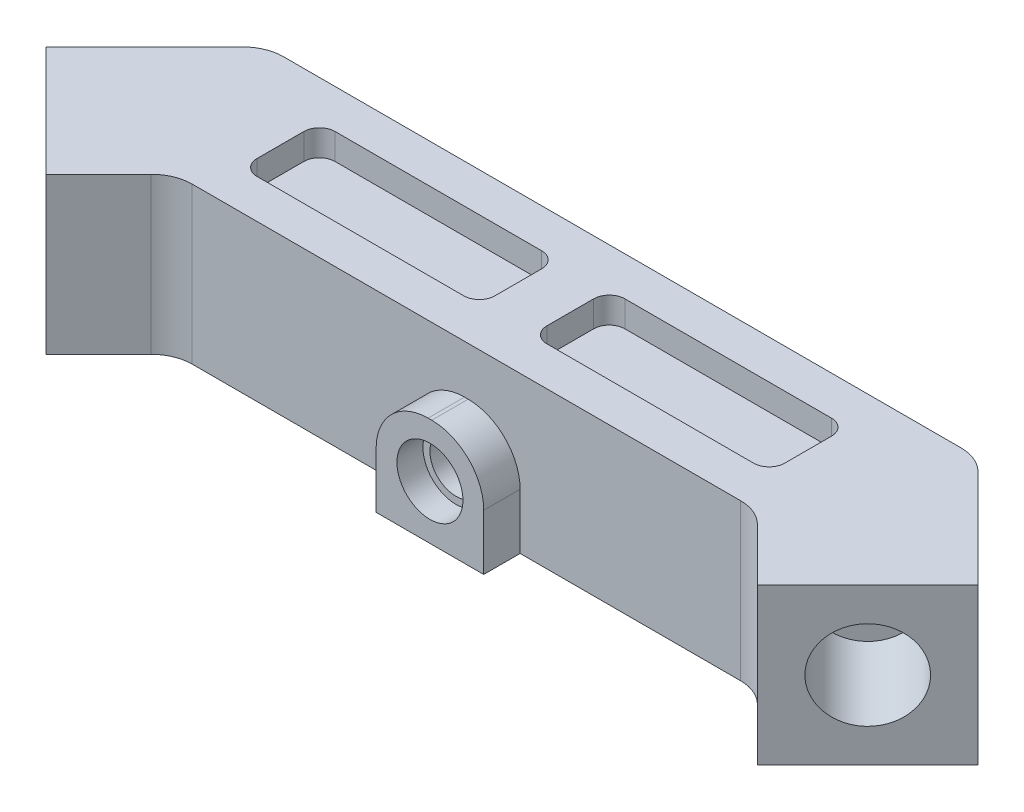
SolidWorks part; units mm, degrees
ref_plane "Front Plane" through (0, 0, 0) normal (0, 0, 1) x (1, 0, 0)
ref_plane "Top Plane" through (0, 0, 0) normal (0, 1, 0) x (1, 0, 0)
ref_plane "Right Plane" through (0, 0, 0) normal (1, 0, 0) x (0, 0, -1)
sketch "Sketch1" plane through (0, 0, 0) normal (0, 1, 0) x (1, 0, 0)
  line L1 (0, 0) -> (142.24, 0)
  line L3 (-15.7815, 38.1) -> (158.0215, 38.1)
  line L5 (0, 0) -> (-15.7815, -15.7815)
  line L6 (-42.7223, 11.1592) -> (-15.7815, -15.7815)
  line L7 (71.12, 38.1) -> (71.12, 0) construction
  line L8 (142.24, 0) -> (158.0215, -15.7815)
  line L9 (184.9623, 11.1592) -> (158.0215, -15.7815)
  line L10 (158.0215, 38.1) -> (184.9623, 11.1592)
  line L11 (-15.7815, 38.1) -> (-42.7223, 11.1592)
  dimension "D1" = 38.1
  dimension "D2" = 135
  dimension "D3" = 38.1
  dimension "D4" = 90
  dimension "D5" = 38.1
  dimension "D6" = 90
  dimension "D7" = 38.1
  dimension "D8" = 38.1
  dimension "D9" = 90
  dimension "D10" = 90
  dimension "D11" = 38.1
  dimension "D12" = 22.3185
  dimension "D13" = 142.24
  dimension "D14" = 173.8031
extrude "Boss-Extrude1" add sketch "Sketch1" along normal blind 38.1
sketch "Sketch2" plane through (-15.7815, 0, 15.7815) normal (-0.7071, 0, 0.7071) x (0.7071, 0, 0.7071)
  line L0 (-38.1, 38.1) -> (0, 0) construction
  line L1 (-38.1, 0) -> (0, 38.1) construction
  circle A0 centre (-19.05, 19.05) radius 10.8585
  dimension "D1" = 21.717
extrude "Cut-Extrude1" cut sketch "Sketch2" against normal blind 25.4
sketch "Sketch3" plane through (86.9015, 0, 86.9015) normal (0.7071, 0, 0.7071) x (0.7071, 0, -0.7071)
  line L0 (100.5789, 38.1) -> (138.6789, 0) construction
  line L1 (100.5789, 0) -> (138.6789, 38.1) construction
  circle A0 centre (119.6289, 19.05) radius 10.8585
  point P11 (119.6289, 19.05)
  dimension "D1" = 21.717
extrude "Cut-Extrude2" cut sketch "Sketch3" against normal blind 25.4
fillet "Fillet1" radius 10 2 edges at (142.24, 19.05, 0) (0, 19.05, 0)
fillet "Fillet2" radius 10 2 edges at (158.0215, 19.05, -38.1) (-15.7815, 19.05, -38.1)
sketch "Sketch5" plane through (0, 0, 0) normal (0, 0, 1) x (1, 0, 0)
  line L0 (4.1421, 0) -> (138.0979, 0) construction
  line L1 (57.9755, 0) -> (84.2645, 0)
  line L2 (57.9755, 0) -> (57.9755, 26.289)
  line L3 (57.9755, 26.289) -> (84.2645, 26.289)
  line L4 (84.2645, 0) -> (84.2645, 26.289)
  line L5 (4.1421, 38.1) -> (138.0979, 38.1) construction
  point P8 (71.12, 38.1)
  point P9 (71.12, 26.289)
  dimension "D1" = 26.289
  dimension "D2" = 26.289
extrude "Boss-Extrude2" add sketch "Sketch5" along normal blind 8.89
sketch "Sketch6" plane through (0, 0, 8.89) normal (0, 0, 1) x (1, 0, 0)
  line L0 (84.2645, 26.289) -> (57.9755, 26.289) construction
  line L1 (57.9755, 26.289) -> (57.9755, 0) construction
  circle A0 centre (71.12, 13.1445) radius 8.0645
  point P4 (71.12, 26.289)
  point P7 (57.9755, 13.1445)
  dimension "D1" = 16.129
extrude "Cut-Extrude3" cut sketch "Sketch6" against normal blind 6.35
sketch "Sketch7" plane through (0, 0, 2.54) normal (0, 0, 1) x (1, 0, 0)
  circle A0 centre (71.12, 13.1445) radius 6.35
  circle A1 centre (71.12, 13.1445) radius 8.0645 construction
  circle A2 centre (71.12, 13.1445) radius 8.0645 construction
  dimension "D1" = 12.7
extrude "Cut-Extrude4" cut sketch "Sketch7" against normal blind 5.08
fillet "Fillet3" radius 12.7 2 edges at (84.2645, 26.289, 4.445) (57.9755, 26.289, 4.445)
sketch "Sketch8" plane through (0, 38.1, 0) normal (0, 1, 0) x (1, 0, 0)
  line L1 (71.12, 58.1794) -> (71.12, 27.1006) construction
  line L2 (153.8794, 38.1) -> (-11.6394, 38.1) construction
  line L3 (28.0687, 0) -> (28.0687, 38.1) construction
  line L4 (6.6653, 28.575) -> (64.77, 28.575)
  line L5 (6.6653, 28.575) -> (6.6653, 9.525)
  line L6 (6.6653, 9.525) -> (64.77, 9.525)
  line L7 (64.77, 28.575) -> (64.77, 9.525)
  line L8 (4.1421, 0) -> (138.0979, 0) construction
  line L9 (135.5747, 9.525) -> (77.47, 9.525)
  line L10 (77.47, 28.575) -> (77.47, 9.525)
  line L11 (135.5747, 28.575) -> (77.47, 28.575)
  line L12 (135.5747, 28.575) -> (135.5747, 9.525)
  arc A0 (4.1421, 0) -> (-2.9289, -2.9289) centre (4.1421, -10) ccw construction
  point P4 (71.12, 38.1)
  point P12 (0.3153, -0.7612)
  point P17 (6.6653, 19.05)
  point P18 (28.0687, 19.05)
  dimension "D1" = 6.35
  dimension "D2" = 6.35
  dimension "D3" = 19.05
extrude "Cut-Extrude5" cut sketch "Sketch8" against normal blind 6.35
fillet "Fillet4" radius 3.81 8 edges at (135.5747, 34.925, -9.525) (77.47, 34.925, -9.525) (64.77, 34.925, -9.525) (6.6653, 34.925, -9.525) (77.47, 34.925, -28.575) (135.5747, 34.925, -28.575) (64.77, 34.925, -28.575) (6.6653, 34.925, -28.575)
